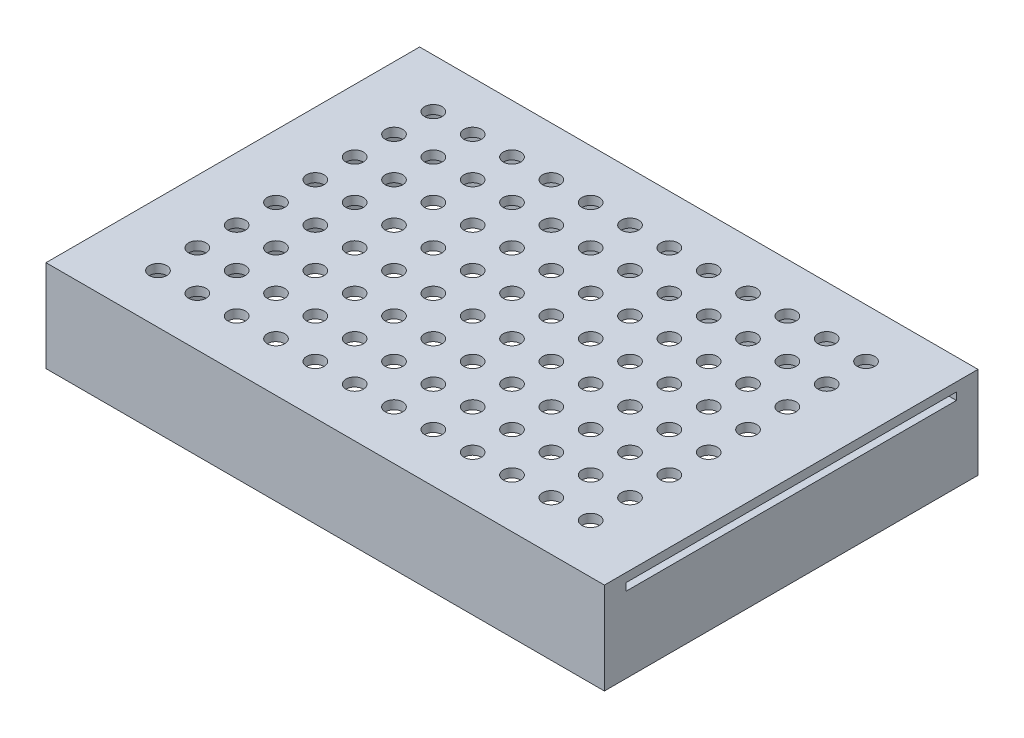
SolidWorks part; units mm, degrees
material "Alliage 6061"
ref_plane "Plan de face" through (0, 0, 0) normal (0, 0, 1) x (1, 0, 0)
ref_plane "Plan de dessus" through (0, 0, 0) normal (0, 1, 0) x (1, 0, 0)
ref_plane "Plan de droite" through (0, 0, 0) normal (1, 0, 0) x (0, 0, -1)
sketch "Esquisse1" plane through (0, 0, 0) normal (0, 1, 0) x (1, 0, 0)
  line L0 (0, -15.2842) -> (0, 12.149) construction
  line L1 (-63.88, 42.74) -> (63.88, 42.74)
  line L2 (-63.88, 42.74) -> (-63.88, -42.74)
  line L3 (-63.88, -42.74) -> (63.88, -42.74)
  line L4 (63.88, 42.74) -> (63.88, -42.74)
  line L5 (-16.068, 0) -> (16.068, 0) construction
  dimension "D1" = 127.76
  dimension "D2" = 85.48
extrude "Base Stock" add sketch "Esquisse1" along normal blind 21
sketch "Esquisse2" plane through (0, 0, 0) normal (0, -1, 0) x (1, 0, 0)
  line L8 (0, -2.9072) -> (0, 5.6823) construction
  line L9 (-55.98, 37.84) -> (55.98, 37.84)
  line L10 (-55.98, 37.84) -> (-55.98, -37.84)
  line L11 (-55.98, -37.84) -> (55.98, -37.84)
  line L12 (55.98, 37.84) -> (55.98, -37.84)
  line L13 (-4.493, 0) -> (7.9287, 0) construction
  line L14 (-63.88, -42.74) -> (-63.88, 42.74) construction
  line L15 (-63.88, 42.74) -> (63.88, 42.74) construction
  dimension "D1" = 7.9
  dimension "D2" = 4.9
extrude "Enlèv. mat.-Extru.2" cut sketch "Esquisse2" against normal blind 19
sketch "Esquisse3" plane through (0, 21, 0) normal (0, 1, 0) x (1, 0, 0)
  circle A0 centre (-49.5, 31.5) radius 2
  circle A1 centre (-40.5, 31.5) radius 2
  circle A2 centre (-31.5, 31.5) radius 2
  circle A3 centre (-22.5, 31.5) radius 2
  circle A4 centre (-13.5, 31.5) radius 2
  circle A5 centre (-4.5, 31.5) radius 2
  circle A6 centre (4.5, 31.5) radius 2
  circle A7 centre (13.5, 31.5) radius 2
  circle A8 centre (22.5, 31.5) radius 2
  circle A9 centre (31.5, 31.5) radius 2
  circle A10 centre (40.5, 31.5) radius 2
  circle A11 centre (49.5, 31.5) radius 2
  circle A12 centre (-40.5, 22.5) radius 2
  circle A13 centre (-31.5, 22.5) radius 2
  circle A14 centre (-22.5, 22.5) radius 2
  circle A15 centre (-13.5, 22.5) radius 2
  circle A16 centre (-4.5, 22.5) radius 2
  circle A17 centre (4.5, 22.5) radius 2
  circle A18 centre (13.5, 22.5) radius 2
  circle A19 centre (22.5, 22.5) radius 2
  circle A20 centre (31.5, 22.5) radius 2
  circle A21 centre (40.5, 22.5) radius 2
  circle A22 centre (49.5, 22.5) radius 2
  circle A23 centre (-40.5, 13.5) radius 2
  circle A24 centre (-31.5, 13.5) radius 2
  circle A25 centre (-22.5, 13.5) radius 2
  circle A26 centre (-13.5, 13.5) radius 2
  circle A27 centre (-4.5, 13.5) radius 2
  circle A28 centre (4.5, 13.5) radius 2
  circle A29 centre (13.5, 13.5) radius 2
  circle A30 centre (22.5, 13.5) radius 2
  circle A31 centre (31.5, 13.5) radius 2
  circle A32 centre (40.5, 13.5) radius 2
  circle A33 centre (49.5, 13.5) radius 2
  circle A34 centre (-40.5, 4.5) radius 2
  circle A35 centre (-31.5, 4.5) radius 2
  circle A36 centre (-22.5, 4.5) radius 2
  circle A37 centre (-13.5, 4.5) radius 2
  circle A38 centre (-4.5, 4.5) radius 2
  circle A39 centre (4.5, 4.5) radius 2
  circle A40 centre (13.5, 4.5) radius 2
  circle A41 centre (22.5, 4.5) radius 2
  circle A42 centre (31.5, 4.5) radius 2
  circle A43 centre (40.5, 4.5) radius 2
  circle A44 centre (49.5, 4.5) radius 2
  circle A45 centre (-40.5, -4.5) radius 2
  circle A46 centre (-31.5, -4.5) radius 2
  circle A47 centre (-22.5, -4.5) radius 2
  circle A48 centre (-13.5, -4.5) radius 2
  circle A49 centre (-4.5, -4.5) radius 2
  circle A50 centre (4.5, -4.5) radius 2
  circle A51 centre (13.5, -4.5) radius 2
  circle A52 centre (22.5, -4.5) radius 2
  circle A53 centre (31.5, -4.5) radius 2
  circle A54 centre (40.5, -4.5) radius 2
  circle A55 centre (49.5, -4.5) radius 2
  circle A56 centre (-40.5, -13.5) radius 2
  circle A57 centre (-31.5, -13.5) radius 2
  circle A58 centre (-22.5, -13.5) radius 2
  circle A59 centre (-13.5, -13.5) radius 2
  circle A60 centre (-4.5, -13.5) radius 2
  circle A61 centre (4.5, -13.5) radius 2
  circle A62 centre (13.5, -13.5) radius 2
  circle A63 centre (22.5, -13.5) radius 2
  circle A64 centre (31.5, -13.5) radius 2
  circle A65 centre (40.5, -13.5) radius 2
  circle A66 centre (49.5, -13.5) radius 2
  circle A67 centre (-40.5, -22.5) radius 2
  circle A68 centre (-31.5, -22.5) radius 2
  circle A69 centre (-22.5, -22.5) radius 2
  circle A70 centre (-13.5, -22.5) radius 2
  circle A71 centre (-4.5, -22.5) radius 2
  circle A72 centre (4.5, -22.5) radius 2
  circle A73 centre (13.5, -22.5) radius 2
  circle A74 centre (22.5, -22.5) radius 2
  circle A75 centre (31.5, -22.5) radius 2
  circle A76 centre (40.5, -22.5) radius 2
  circle A77 centre (49.5, -22.5) radius 2
  circle A78 centre (-40.5, -31.5) radius 2
  circle A79 centre (-31.5, -31.5) radius 2
  circle A80 centre (-22.5, -31.5) radius 2
  circle A81 centre (-13.5, -31.5) radius 2
  circle A82 centre (-4.5, -31.5) radius 2
  circle A83 centre (4.5, -31.5) radius 2
  circle A84 centre (13.5, -31.5) radius 2
  circle A85 centre (22.5, -31.5) radius 2
  circle A86 centre (31.5, -31.5) radius 2
  circle A87 centre (40.5, -31.5) radius 2
  circle A88 centre (49.5, -31.5) radius 2
  circle A89 centre (-49.5, 22.5) radius 2
  circle A90 centre (-49.5, 13.5) radius 2
  circle A91 centre (-49.5, 4.5) radius 2
  circle A92 centre (-49.5, -4.5) radius 2
  circle A93 centre (-49.5, -13.5) radius 2
  circle A94 centre (-49.5, -22.5) radius 2
  circle A95 centre (-49.5, -31.5) radius 2
  dimension "D3" = 4
  dimension "D1" = 49.5
  dimension "D2" = 31.5
  dimension "D4" = 12
  dimension "D5" = 8
extrude "Vial Holes" cut sketch "Esquisse3" against normal through all
fillet "Congé1" radius 5 4 edges at (55.98, 9.5, 37.84) (55.98, 9.5, -37.84) (-55.98, 9.5, 37.84) (-55.98, 9.5, -37.84)
sketch "Esquisse5" plane through (0, 0, 0) normal (0, -1, 0) x (1, 0, 0)
  line L0 (-63.88, 42.74) -> (63.88, 42.74) construction
  line L1 (-63.88, -42.74) -> (-63.88, 42.74) construction
  line L2 (-29.965, 16.9119) -> (-29.965, 27.7674) construction
  line L3 (-26.4639, 20.145) -> (-36.5759, 20.145) construction
  line L4 (0, 9.4766) -> (0, -5.5427) construction
  line L5 (6.8462, 0) -> (-9.5114, 0) construction
  circle A0 centre (-59.93, 40.29) radius 1.55
  circle A2 centre (0, 40.29) radius 1.55
  circle A4 centre (-59.93, 0) radius 1.55
  circle A5 centre (59.93, 0) radius 1.55
  circle A8 centre (59.93, 40.29) radius 1.55
  circle A9 centre (59.93, -40.29) radius 1.55
  circle A13 centre (0, -40.29) radius 1.55
  circle A15 centre (-59.93, -40.29) radius 1.55
  dimension "D3" = 3.1
  dimension "D1" = 2.45
  dimension "D2" = 3.95
extrude "Magnet Holes" cut sketch "Esquisse5" against normal blind 3
chamfer "Magnet Holes Chamfer" distance 0.2 angle 45 8 edges at (-59.93, 0, -1.55) (-59.93, 0, -38.74) (0, 0, -38.74) (59.93, 0, -41.84) (59.93, 0, 1.55) (59.93, 0, 41.84) (0, 0, 38.74) (-59.93, 0, 38.74)
sketch "Esquisse6" plane through (0, 3, 0) normal (0, -1, 0) x (1, 0, 0)
  circle A0 centre (-59.93, 0) radius 0.75
  circle A1 centre (-59.93, 40.29) radius 0.75
  circle A2 centre (0, 40.29) radius 0.75
  circle A3 centre (59.93, 40.29) radius 0.75
  circle A4 centre (59.93, 0) radius 0.75
  circle A5 centre (59.93, -40.29) radius 0.75
  circle A6 centre (0, -40.29) radius 0.75
  circle A7 centre (-59.93, -40.29) radius 0.75
  dimension "D1" = 1.5
extrude "Magnet Holes Air" cut sketch "Esquisse6" against normal blind 2
sketch "Esquisse7" plane through (-63.88, 0, 0) normal (1, 0, 0) x (0, 0, -1)
  line L1 (-37.8, 19) -> (37.8, 19)
  line L2 (-37.8, 19) -> (-37.8, 17.3)
  line L3 (-37.8, 17.3) -> (37.8, 17.3)
  line L4 (32.84, 19) -> (-32.84, 19)
  line L5 (-32.84, 19) -> (-32.84, 0)
  line L6 (-32.84, 0) -> (32.84, 0)
  line L7 (32.84, 0) -> (32.84, 19)
  line L8 (32.84, 19) -> (-32.84, 19) construction
  line L12 (37.8, 19) -> (37.8, 17.3)
  point P8 (0, 19)
  dimension "D2" = 75.6
  dimension "D3" = 1.7
  dimension "D1" = 0
extrude "Enlèv. mat.-Extru.3" cut sketch "Esquisse7" along normal through all
